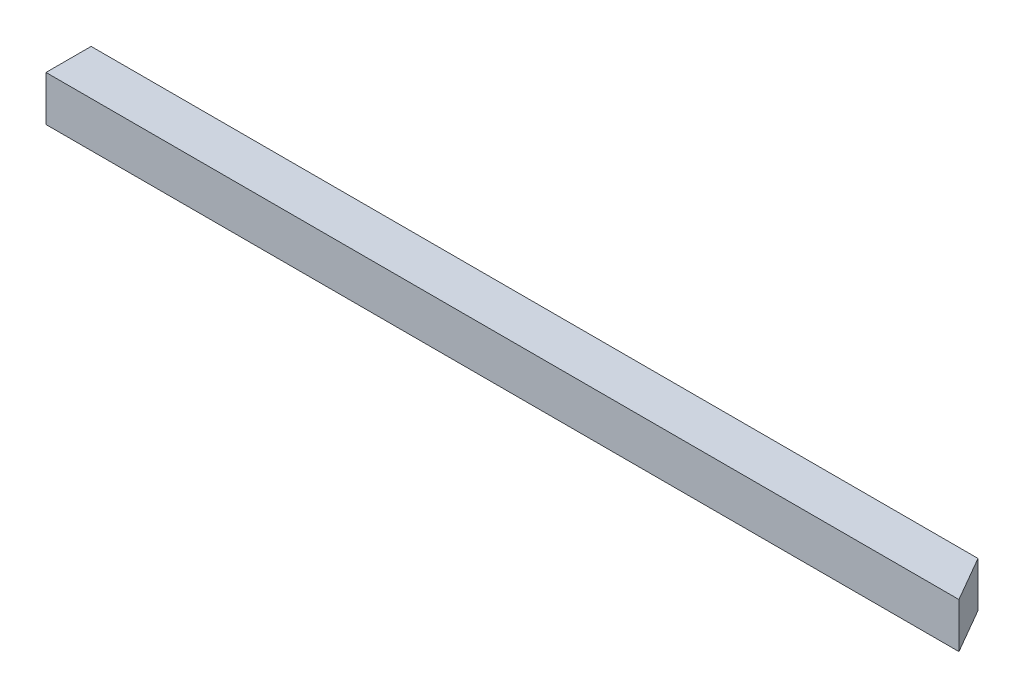
SolidWorks part; units mm, degrees
ref_plane "前视基准面" through (0, 0, 0) normal (0, 0, 1) x (1, 0, 0)
ref_plane "上视基准面" through (0, 0, 0) normal (0, 1, 0) x (1, 0, 0)
ref_plane "右视基准面" through (0, 0, 0) normal (1, 0, 0) x (0, 0, -1)
sketch "草图1" plane through (0, 0, 0) normal (0, 1, 0) x (1, 0, 0)
  line L0 (-600, -200) -> (600, -200) construction
  line L5 (480, -563.7307) -> (503.094, -563.7307)
  line L6 (110, -563.7307) -> (480, -563.7307)
  line L7 (110, -563.7307) -> (-100, -200) construction
  line L8 (110, -563.7307) -> (110, -583.7307)
  line L9 (110, -583.7307) -> (480, -583.7307)
  line L10 (503.094, -563.7307) -> (514.641, -583.7307)
  line L11 (514.641, -583.7307) -> (480, -583.7307)
  line L12 (480, -563.7307) -> (491.547, -583.7307) construction
  point P8 (0, -200)
  dimension "D1" = 20
  dimension "D2" = 200
  dimension "D3" = 60
  dimension "D4" = 1200
  dimension "D5" = 500
  dimension "D6" = 420
  dimension "D7" = 370
  dimension "D8" = 60
  dimension "D9" = 20
extrude "凸台-拉伸1" add sketch "草图1" along normal blind 20
